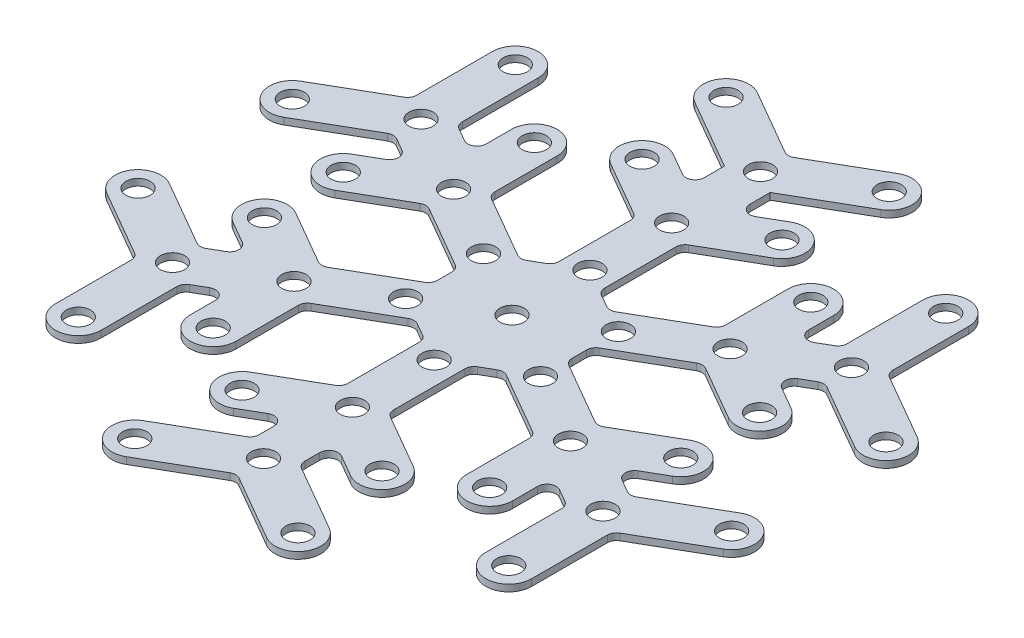
SolidWorks part; units mm, degrees
ref_plane "Front Plane" through (0, 0, 0) normal (0, 0, 1) x (1, 0, 0)
ref_plane "Top Plane" through (0, 0, 0) normal (0, 1, 0) x (1, 0, 0)
ref_plane "Right Plane" through (0, 0, 0) normal (1, 0, 0) x (0, 0, -1)
sketch "Sketch1" plane through (0, 0, 0) normal (0, 1, 0) x (1, 0, 0)
  line L0 (0, 117.2283) -> (38.4948, 139.4533) construction
  line L1 (0, 117.2283) -> (-38.4948, 139.4533) construction
  line L2 (0, 152.4) -> (0, -152.4) construction
  line L3 (-33.0973, 148.802) -> (-2.1749, 130.9489)
  line L4 (2.1749, 130.9489) -> (33.0973, 148.802)
  line L5 (-32.9956, 94.3448) -> (0, 75.2948) construction
  line L6 (0, 75.2948) -> (32.9956, 94.3448) construction
  line L7 (-18.8395, 25.8533) -> (-12.9699, 29.2422)
  line L8 (-152.4, 152.4) -> (152.4, 152.4) construction
  line L9 (-152.4, 152.4) -> (-152.4, -152.4) construction
  line L10 (-152.4, -152.4) -> (152.4, -152.4) construction
  line L11 (152.4, 152.4) -> (152.4, -152.4) construction
  line L12 (10.795, 110.9958) -> (10.795, 101.5262)
  line L13 (-10.795, 110.9958) -> (-10.795, 101.5262)
  line L14 (-27.5981, 103.6935) -> (-17.3196, 97.7592)
  line L15 (27.5981, 103.6935) -> (17.3196, 97.7592)
  line L16 (-38.3931, 84.996) -> (-12.9699, 70.3179)
  line L17 (12.9699, 70.3179) -> (38.3931, 84.996)
  line L18 (-43.8923, 130.1045) -> (-10.795, 110.9958)
  line L19 (10.795, 110.9958) -> (43.8923, 130.1045)
  line L20 (10.795, 66.5509) -> (10.795, 33.0091)
  line L21 (-10.795, 66.5509) -> (-10.795, 33.0091)
  line L22 (112.3177, 103.0641) -> (112.3177, 67.358)
  line L23 (114.4925, 63.591) -> (145.415, 45.7379)
  line L24 (99.3478, 44.8935) -> (93.3218, 41.4144)
  line L25 (88.5528, 63.591) -> (82.5268, 60.1118)
  line L26 (76.0022, 75.7474) -> (76.0022, 63.8788)
  line L27 (103.6002, 27.9461) -> (93.3218, 33.8804)
  line L28 (54.4122, 75.7474) -> (54.4122, 46.3912)
  line L29 (67.382, 23.9267) -> (92.8052, 9.2486)
  line L30 (90.7277, 103.0641) -> (90.7277, 67.358)
  line L31 (103.6975, 44.8935) -> (134.62, 27.0404)
  line L32 (63.0323, 23.9267) -> (33.9843, 7.1558)
  line L33 (52.2373, 42.6242) -> (23.1893, 25.8533)
  line L34 (101.5227, 58.6141) -> (140.0175, 36.3891) construction
  line L35 (101.5227, 58.6141) -> (101.5227, 103.0641) construction
  line L36 (65.2072, 75.7474) -> (65.2072, 37.6474) construction
  line L37 (65.2072, 37.6474) -> (98.2027, 18.5974) construction
  line L38 (145.415, -45.7379) -> (114.4925, -63.591)
  line L39 (112.3177, -67.358) -> (112.3177, -103.0641)
  line L40 (88.5528, -63.591) -> (82.5268, -60.1118)
  line L41 (99.3478, -44.8935) -> (93.3218, -41.4144)
  line L42 (103.6002, -27.9461) -> (93.3218, -33.8804)
  line L43 (76.0022, -75.7474) -> (76.0022, -63.8788)
  line L44 (92.8052, -9.2486) -> (67.382, -23.9267)
  line L45 (54.4122, -46.3912) -> (54.4122, -75.7474)
  line L46 (134.62, -27.0404) -> (103.6975, -44.8935)
  line L47 (90.7277, -67.358) -> (90.7277, -103.0641)
  line L48 (52.2373, -42.6242) -> (23.1893, -25.8533)
  line L49 (63.0323, -23.9267) -> (33.9843, -7.1558)
  line L50 (101.5227, -58.6141) -> (101.5227, -103.0641) construction
  line L51 (101.5227, -58.6141) -> (140.0175, -36.3891) construction
  line L52 (98.2027, -18.5974) -> (65.2072, -37.6474) construction
  line L53 (65.2072, -37.6474) -> (65.2072, -75.7474) construction
  line L54 (33.0973, -148.802) -> (2.1749, -130.9489)
  line L55 (-2.1749, -130.9489) -> (-33.0973, -148.802)
  line L56 (-10.795, -108.4845) -> (-10.795, -101.5262)
  line L57 (10.795, -108.4845) -> (10.795, -101.5262)
  line L58 (27.5981, -103.6935) -> (17.3196, -97.7592)
  line L59 (-27.5981, -103.6935) -> (-17.3196, -97.7592)
  line L60 (38.3931, -84.996) -> (12.9699, -70.3179)
  line L61 (-12.9699, -70.3179) -> (-38.3931, -84.996)
  line L62 (43.8923, -130.1045) -> (12.9699, -112.2514)
  line L63 (-12.9699, -112.2514) -> (-43.8923, -130.1045)
  line L64 (-10.795, -66.5509) -> (-10.795, -33.0091)
  line L65 (10.795, -66.5509) -> (10.795, -33.0091)
  line L66 (0, -117.2283) -> (-38.4948, -139.4533) construction
  line L67 (0, -117.2283) -> (38.4948, -139.4533) construction
  line L68 (32.9956, -94.3448) -> (0, -75.2948) construction
  line L69 (0, -75.2948) -> (-32.9956, -94.3448) construction
  line L70 (-112.3177, -103.0641) -> (-112.3177, -67.358)
  line L71 (-114.4925, -63.591) -> (-145.415, -45.7379)
  line L72 (-99.3478, -44.8935) -> (-93.3218, -41.4144)
  line L73 (-88.5528, -63.591) -> (-82.5268, -60.1118)
  line L74 (-76.0022, -75.7474) -> (-76.0022, -63.8788)
  line L75 (-103.6002, -27.9461) -> (-93.3218, -33.8804)
  line L76 (-54.4122, -75.7474) -> (-54.4122, -46.3912)
  line L77 (-67.382, -23.9267) -> (-92.8052, -9.2486)
  line L78 (-90.7277, -103.0641) -> (-90.7277, -67.358)
  line L79 (-103.6975, -44.8935) -> (-134.62, -27.0404)
  line L80 (-63.0323, -23.9267) -> (-33.9843, -7.1558)
  line L81 (-52.2373, -42.6242) -> (-23.1893, -25.8533)
  line L82 (-101.5227, -58.6141) -> (-140.0175, -36.3891) construction
  line L83 (-101.5227, -58.6141) -> (-101.5227, -103.0641) construction
  line L84 (-65.2072, -75.7474) -> (-65.2072, -37.6474) construction
  line L85 (-65.2072, -37.6474) -> (-98.2027, -18.5974) construction
  line L86 (-145.415, 45.7379) -> (-114.4925, 63.591)
  line L87 (-112.3177, 67.358) -> (-112.3177, 103.0641)
  line L88 (-88.5528, 63.591) -> (-82.5268, 60.1118)
  line L89 (-99.3478, 44.8935) -> (-93.3218, 41.4144)
  line L90 (-103.6002, 27.9461) -> (-93.3218, 33.8804)
  line L91 (-76.0022, 75.7474) -> (-76.0022, 63.8788)
  line L92 (-92.8052, 9.2486) -> (-67.382, 23.9267)
  line L93 (-54.4122, 46.3912) -> (-54.4122, 75.7474)
  line L94 (-134.62, 27.0404) -> (-103.6975, 44.8935)
  line L95 (-90.7277, 67.358) -> (-90.7277, 103.0641)
  line L96 (-52.2373, 42.6242) -> (-23.1893, 25.8533)
  line L97 (-63.0323, 23.9267) -> (-33.9843, 7.1558)
  line L98 (-101.5227, 58.6141) -> (-101.5227, 103.0641) construction
  line L99 (-101.5227, 58.6141) -> (-140.0175, 36.3891) construction
  line L100 (-98.2027, 18.5974) -> (-65.2072, 37.6474) construction
  line L101 (-65.2072, 37.6474) -> (-65.2072, 75.7474) construction
  line L109 (-101.5227, 58.6141) -> (101.5227, -58.6141) construction
  line L113 (150.8125, 92.4582) -> (150.8125, 6.7638) construction
  line L117 (-152.4, 0) -> (152.4, 0) construction
  line L121 (-101.5227, -58.6141) -> (101.5227, 58.6141) construction
  line L124 (0, 36.7303) -> (-31.8094, 18.3652) construction
  line L125 (-31.8094, 18.3652) -> (-31.8094, -18.3652) construction
  line L126 (-31.8094, -18.3652) -> (0, -36.7303) construction
  line L127 (0, -36.7303) -> (31.8094, -18.3652) construction
  line L128 (31.8094, -18.3652) -> (31.8094, 18.3652) construction
  line L129 (31.8094, 18.3652) -> (0, 36.7303) construction
  line L130 (12.9699, 29.2422) -> (18.8395, 25.8533)
  line L131 (31.8094, 3.3889) -> (31.8094, -3.3889)
  line L132 (18.8395, -25.8533) -> (12.9699, -29.2422)
  line L133 (-12.9699, -29.2422) -> (-18.8395, -25.8533)
  line L134 (-31.8094, 3.3889) -> (-31.8094, -3.3889)
  circle A0 centre (0, 117.2283) radius 5.715
  circle A1 centre (0, 117.2283) radius 10.795 construction
  circle A2 centre (38.4948, 139.4533) radius 5.715
  arc A3 (43.8923, 130.1045) -> (33.0973, 148.802) centre (38.4948, 139.4533) ccw
  circle A4 centre (-38.4948, 139.4533) radius 5.715
  arc A5 (-33.0973, 148.802) -> (-43.8923, 130.1045) centre (-38.4948, 139.4533) ccw
  circle A6 centre (-32.9956, 94.3448) radius 5.715
  circle A7 centre (32.9956, 94.3448) radius 5.715
  arc A9 (-27.5981, 103.6935) -> (-38.3931, 84.996) centre (-32.9956, 94.3448) ccw
  arc A10 (38.3931, 84.996) -> (27.5981, 103.6935) centre (32.9956, 94.3448) ccw
  circle A11 centre (101.5227, 58.6141) radius 5.715
  circle A12 centre (101.5227, 58.6141) radius 10.795 construction
  circle A13 centre (140.0175, 36.3891) radius 5.715
  arc A14 (134.62, 27.0404) -> (145.415, 45.7379) centre (140.0175, 36.3891) ccw
  circle A15 centre (101.5227, 103.0641) radius 5.715
  arc A16 (112.3177, 103.0641) -> (90.7277, 103.0641) centre (101.5227, 103.0641) ccw
  circle A17 centre (65.2072, 75.7474) radius 5.715
  circle A18 centre (98.2027, 18.5974) radius 5.715
  arc A19 (76.0022, 75.7474) -> (54.4122, 75.7474) centre (65.2072, 75.7474) ccw
  arc A20 (92.8052, 9.2486) -> (103.6002, 27.9461) centre (98.2027, 18.5974) ccw
  circle A21 centre (101.5227, -58.6141) radius 5.715
  circle A22 centre (101.5227, -58.6141) radius 10.795 construction
  circle A23 centre (101.5227, -103.0641) radius 5.715
  arc A24 (90.7277, -103.0641) -> (112.3177, -103.0641) centre (101.5227, -103.0641) ccw
  circle A25 centre (140.0175, -36.3891) radius 5.715
  arc A26 (145.415, -45.7379) -> (134.62, -27.0404) centre (140.0175, -36.3891) ccw
  circle A27 centre (98.2027, -18.5974) radius 5.715
  circle A28 centre (65.2072, -75.7474) radius 5.715
  arc A29 (103.6002, -27.9461) -> (92.8052, -9.2486) centre (98.2027, -18.5974) ccw
  arc A30 (54.4122, -75.7474) -> (76.0022, -75.7474) centre (65.2072, -75.7474) ccw
  circle A31 centre (0, -117.2283) radius 5.715
  circle A32 centre (0, -117.2283) radius 10.795 construction
  circle A33 centre (-38.4948, -139.4533) radius 5.715
  arc A34 (-43.8923, -130.1045) -> (-33.0973, -148.802) centre (-38.4948, -139.4533) ccw
  circle A35 centre (38.4948, -139.4533) radius 5.715
  arc A36 (33.0973, -148.802) -> (43.8923, -130.1045) centre (38.4948, -139.4533) ccw
  circle A37 centre (32.9956, -94.3448) radius 5.715
  circle A38 centre (-32.9956, -94.3448) radius 5.715
  arc A39 (27.5981, -103.6935) -> (38.3931, -84.996) centre (32.9956, -94.3448) ccw
  arc A40 (-38.3931, -84.996) -> (-27.5981, -103.6935) centre (-32.9956, -94.3448) ccw
  circle A41 centre (-101.5227, -58.6141) radius 5.715
  circle A42 centre (-101.5227, -58.6141) radius 10.795 construction
  circle A43 centre (-140.0175, -36.3891) radius 5.715
  arc A44 (-134.62, -27.0404) -> (-145.415, -45.7379) centre (-140.0175, -36.3891) ccw
  circle A45 centre (-101.5227, -103.0641) radius 5.715
  arc A46 (-112.3177, -103.0641) -> (-90.7277, -103.0641) centre (-101.5227, -103.0641) ccw
  circle A47 centre (-65.2072, -75.7474) radius 5.715
  circle A48 centre (-98.2027, -18.5974) radius 5.715
  arc A49 (-76.0022, -75.7474) -> (-54.4122, -75.7474) centre (-65.2072, -75.7474) ccw
  arc A50 (-92.8052, -9.2486) -> (-103.6002, -27.9461) centre (-98.2027, -18.5974) ccw
  circle A51 centre (-101.5227, 58.6141) radius 5.715
  circle A52 centre (-101.5227, 58.6141) radius 10.795 construction
  circle A53 centre (-101.5227, 103.0641) radius 5.715
  arc A54 (-90.7277, 103.0641) -> (-112.3177, 103.0641) centre (-101.5227, 103.0641) ccw
  circle A55 centre (-140.0175, 36.3891) radius 5.715
  arc A56 (-145.415, 45.7379) -> (-134.62, 27.0404) centre (-140.0175, 36.3891) ccw
  circle A57 centre (-98.2027, 18.5974) radius 5.715
  circle A58 centre (-65.2072, 75.7474) radius 5.715
  arc A59 (-103.6002, 27.9461) -> (-92.8052, 9.2486) centre (-98.2027, 18.5974) ccw
  arc A60 (-54.4122, 75.7474) -> (-76.0022, 75.7474) centre (-65.2072, 75.7474) ccw
  circle A61 centre (-65.2072, 37.6474) radius 5.715
  circle A62 centre (0, 75.2948) radius 5.715
  circle A63 centre (65.2072, 37.6474) radius 5.715
  circle A64 centre (65.2072, -37.6474) radius 5.715
  circle A65 centre (0, -75.2948) radius 5.715
  circle A66 centre (-65.2072, -37.6474) radius 5.715
  circle A67 centre (0, 0) radius 5.715
  circle A68 centre (31.8094, -18.3652) radius 5.715
  circle A69 centre (0, 36.7303) radius 5.715
  circle A70 centre (-31.8094, -18.3652) radius 5.715
  circle A71 centre (-31.8094, 18.3652) radius 5.715
  circle A72 centre (0, -36.7303) radius 5.715
  circle A73 centre (31.8094, 18.3652) radius 5.715
  circle A74 centre (0, 0) radius 31.8094 construction
  arc A75 (-17.3196, 97.7592) -> (-10.795, 101.5262) centre (-15.1447, 101.5262) ccw
  arc A76 (17.3196, 97.7592) -> (10.795, 101.5262) centre (15.1447, 101.5262) cw
  arc A77 (-2.1749, 130.9489) -> (2.1749, 130.9489) centre (0, 134.7159) ccw
  arc A78 (12.9699, 70.3179) -> (10.795, 66.5509) centre (15.1447, 66.5509) ccw
  arc A79 (-12.9699, 70.3179) -> (-10.795, 66.5509) centre (-15.1447, 66.5509) cw
  arc A80 (-23.1893, 25.8533) -> (-18.8395, 25.8533) centre (-21.0144, 29.6203) ccw
  arc A81 (-10.795, 33.0091) -> (-12.9699, 29.2422) centre (-15.1447, 33.0091) cw
  arc A82 (10.795, 33.0091) -> (12.9699, 29.2422) centre (15.1447, 33.0091) ccw
  arc A83 (23.1893, 25.8533) -> (18.8395, 25.8533) centre (21.0144, 29.6203) cw
  arc A84 (54.4122, 46.3912) -> (52.2373, 42.6242) centre (50.0624, 46.3912) cw
  arc A85 (82.5268, 60.1118) -> (76.0022, 63.8788) centre (80.3519, 63.8788) cw
  arc A86 (88.5528, 63.591) -> (90.7277, 67.358) centre (86.3779, 67.358) ccw
  arc A87 (112.3177, 67.358) -> (114.4925, 63.591) centre (116.6674, 67.358) ccw
  arc A88 (99.3478, 44.8935) -> (103.6975, 44.8935) centre (101.5227, 41.1265) cw
  arc A89 (93.3218, 41.4144) -> (93.3218, 33.8804) centre (95.4966, 37.6474) ccw
  arc A90 (67.382, 23.9267) -> (63.0323, 23.9267) centre (65.2072, 20.1598) ccw
  arc A91 (33.9843, 7.1558) -> (31.8094, 3.3889) centre (36.1591, 3.3889) ccw
  arc A92 (33.9843, -7.1558) -> (31.8094, -3.3889) centre (36.1591, -3.3889) cw
  arc A93 (67.382, -23.9267) -> (63.0323, -23.9267) centre (65.2072, -20.1598) cw
  arc A94 (93.3218, -41.4144) -> (93.3218, -33.8804) centre (95.4966, -37.6474) cw
  arc A95 (99.3478, -44.8935) -> (103.6975, -44.8935) centre (101.5227, -41.1265) ccw
  arc A96 (114.4925, -63.591) -> (112.3177, -67.358) centre (116.6674, -67.358) ccw
  arc A97 (88.5528, -63.591) -> (90.7277, -67.358) centre (86.3779, -67.358) cw
  arc A98 (82.5268, -60.1118) -> (76.0022, -63.8788) centre (80.3519, -63.8788) ccw
  arc A99 (54.4122, -46.3912) -> (52.2373, -42.6242) centre (50.0624, -46.3912) ccw
  arc A100 (18.8395, -25.8533) -> (23.1893, -25.8533) centre (21.0144, -29.6203) cw
  arc A101 (10.795, -33.0091) -> (12.9699, -29.2422) centre (15.1447, -33.0091) cw
  arc A102 (12.9699, -70.3179) -> (10.795, -66.5509) centre (15.1447, -66.5509) cw
  arc A103 (10.795, -101.5262) -> (17.3196, -97.7592) centre (15.1447, -101.5262) cw
  arc A104 (10.795, -108.4845) -> (12.9699, -112.2514) centre (15.1447, -108.4845) ccw
  arc A105 (2.1749, -130.9489) -> (-2.1749, -130.9489) centre (0, -134.7159) ccw
  arc A106 (-10.795, -108.4845) -> (-12.9699, -112.2514) centre (-15.1447, -108.4845) cw
  arc A107 (-10.795, -101.5262) -> (-17.3196, -97.7592) centre (-15.1447, -101.5262) ccw
  arc A108 (-12.9699, -70.3179) -> (-10.795, -66.5509) centre (-15.1447, -66.5509) ccw
  arc A109 (-12.9699, -29.2422) -> (-10.795, -33.0091) centre (-15.1447, -33.0091) cw
  arc A110 (-23.1893, -25.8533) -> (-18.8395, -25.8533) centre (-21.0144, -29.6203) cw
  arc A111 (-54.4122, -46.3912) -> (-52.2373, -42.6242) centre (-50.0624, -46.3912) cw
  arc A112 (-82.5268, -60.1118) -> (-76.0022, -63.8788) centre (-80.3519, -63.8788) cw
  arc A113 (-88.5528, -63.591) -> (-90.7277, -67.358) centre (-86.3779, -67.358) ccw
  arc A114 (-112.3177, -67.358) -> (-114.4925, -63.591) centre (-116.6674, -67.358) ccw
  arc A115 (-99.3478, -44.8935) -> (-103.6975, -44.8935) centre (-101.5227, -41.1265) cw
  arc A116 (-93.3218, -41.4144) -> (-93.3218, -33.8804) centre (-95.4966, -37.6474) ccw
  arc A117 (-67.382, -23.9267) -> (-63.0323, -23.9267) centre (-65.2072, -20.1598) ccw
  arc A118 (-33.9843, -7.1558) -> (-31.8094, -3.3889) centre (-36.1591, -3.3889) ccw
  arc A119 (-33.9843, 7.1558) -> (-31.8094, 3.3889) centre (-36.1591, 3.3889) cw
  arc A120 (-67.382, 23.9267) -> (-63.0323, 23.9267) centre (-65.2072, 20.1598) cw
  arc A121 (-54.4122, 46.3912) -> (-52.2373, 42.6242) centre (-50.0624, 46.3912) ccw
  arc A122 (-82.5268, 60.1118) -> (-76.0022, 63.8788) centre (-80.3519, 63.8788) ccw
  arc A123 (-93.3218, 41.4144) -> (-93.3218, 33.8804) centre (-95.4966, 37.6474) cw
  arc A124 (-99.3478, 44.8935) -> (-103.6975, 44.8935) centre (-101.5227, 41.1265) ccw
  arc A125 (-114.4925, 63.591) -> (-112.3177, 67.358) centre (-116.6674, 67.358) ccw
  arc A126 (-88.5528, 63.591) -> (-90.7277, 67.358) centre (-86.3779, 67.358) cw
  point P10 (0, 0)
  point P20 (-152.4, 0)
  point P27 (0, 152.4)
  point P54 (0, 129.6933)
  point P64 (10.795, 69.0623)
  point P96 (-10.795, 69.0623)
  point P122 (-21.0144, 24.5977)
  point P155 (-10.795, 30.4978)
  point P188 (10.795, 30.4978)
  point P199 (21.0144, 24.5977)
  point P215 (0, 0)
  point P232 (0, -152.4)
  point P252 (31.8094, 5.9002)
  point P255 (31.8094, -5.9002)
  point P274 (10.795, -30.4978)
  point P291 (-10.795, -30.4978)
  point P294 (-21.0144, -24.5977)
  point P311 (-31.8094, -5.9002)
  point P314 (-31.8094, 5.9002)
  dimension "D1" = 11.43
  dimension "D2" = 5.08
  dimension "D13" = 4.3497
  dimension "D3" = 60
  dimension "D4" = 60
  dimension "D5" = 44.45
  dimension "D6" = 60
  dimension "D7" = 60
  dimension "D8" = 38.1
  dimension "D9" = 304.8
  dimension "D10" = 304.8
  dimension "D12" = 1.5875
  dimension "D11" = 6
extrude "Boss-Extrude1" add sketch "Sketch1" along normal blind 3.175
